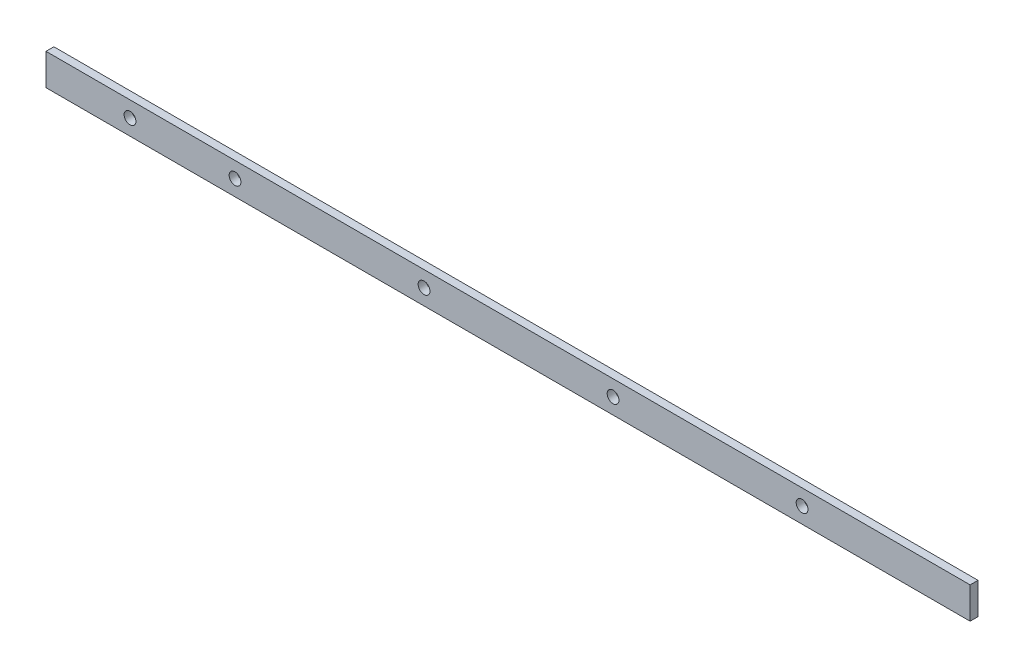
SolidWorks part; units mm, degrees
ref_plane "Front Plane" through (0, 0, 0) normal (0, 0, 1) x (1, 0, 0)
ref_plane "Top Plane" through (0, 0, 0) normal (0, 1, 0) x (1, 0, 0)
ref_plane "Right Plane" through (0, 0, 0) normal (1, 0, 0) x (0, 0, -1)
sketch "Sketch1" plane through (0, 0, 0) normal (0, 0, 1) x (1, 0, 0)
  line L1 (0, 0) -> (558.8, 0)
  line L2 (0, 0) -> (0, 19.05)
  line L3 (0, 19.05) -> (558.8, 19.05)
  line L4 (558.8, 0) -> (558.8, 19.05)
extrude "Boss-Extrude1" add sketch "Sketch1" along normal blind 4.7752
sketch "Sketch2" plane through (0, 0, 0) normal (0, 0, 1) x (1, 0, 0)
  circle A0 centre (50.8, 9.525) radius 3.5687
  circle A1 centre (114.3, 9.525) radius 3.5687
  circle A2 centre (228.6, 9.525) radius 3.5687
  circle A3 centre (342.9, 9.525) radius 3.5687
  circle A4 centre (457.2, 9.525) radius 3.5687
extrude "Cut-Extrude1" cut sketch "Sketch2" along normal through all
